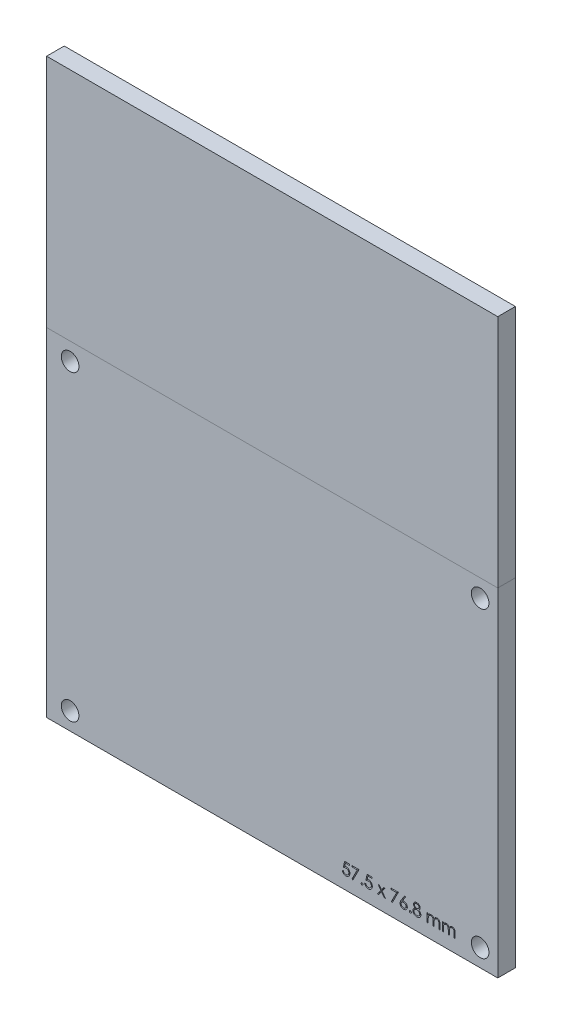
SolidWorks part; units mm, degrees
ref_plane "Front Plane" through (0, 0, 0) normal (0, 0, 1) x (1, 0, 0)
ref_plane "Top Plane" through (0, 0, 0) normal (0, 1, 0) x (1, 0, 0)
ref_plane "Right Plane" through (0, 0, 0) normal (1, 0, 0) x (0, 0, -1)
sketch "Sketch1" plane through (0, 0, 0) normal (0, 0, 1) x (1, 0, 0)
  line L1 (-38.4, 28.75) -> (38.4, 28.75)
  line L2 (-38.4, 28.75) -> (-38.4, -28.75)
  line L3 (-38.4, -28.75) -> (38.4, -28.75)
  line L4 (38.4, 28.75) -> (38.4, -28.75)
  line L5 (-38.4, 28.75) -> (38.4, -28.75) construction
  line L6 (-38.4, -28.75) -> (38.4, 28.75) construction
  dimension "D1" = 57.5
  dimension "D2" = 76.8
  dimension "D3" = 28.75
  dimension "D4" = 38.4
extrude "Boss-Extrude1" add sketch "Sketch1" along normal blind 3 contours L1 L4 L3 L2
sketch "Sketch2" plane through (0, 0, 3) normal (0, 0, 1) x (1, 0, 0)
  line L0 (1.65, 0) -> (-1.65, 0) construction
  line L3 (38.4, 28.75) -> (38.4, -28.75) construction
  line L6 (-38.4, -28.75) -> (38.4, -28.75) construction
  line L7 (-38.4, 28.75) -> (38.4, 28.75) construction
  line L9 (-38.4, 28.75) -> (-38.4, -28.75) construction
  circle A0 centre (-34.4, 25.75) radius 1.5
  circle A1 centre (-34.4, -25.75) radius 1.5
  circle A4 centre (35.4, 25.75) radius 1.5
  circle A5 centre (35.4, -25.75) radius 1.5
  dimension "D1" = 3
  dimension "D2" = 1.5
  dimension "D3" = 2.5
  dimension "D4" = 3
  dimension "D5" = 3
  dimension "D6" = 1.5
  dimension "D7" = 1.5
  dimension "D8" = 1.5
  dimension "D9" = 1.5
extrude "Cut-Extrude1" cut sketch "Sketch2" against normal through all both and the other way through all
sketch "Sketch4" plane through (0, 0, 3) normal (0, 0, 1) x (1, 0, 0)
  text T0 "57.5 x 76.8 mm\r\n" font "Century Gothic" height 2
extrude "Cut-Extrude2" cut sketch "Sketch4" against normal blind 1
sketch "Sketch5" plane through (0, 28.75, 0) normal (0, 1, 0) x (1, 0, 0)
  line L1 (38.4, -3) -> (-38.4, -3)
  line L2 (38.4, -3) -> (38.4, 0)
  line L3 (38.4, 0) -> (-38.4, 0)
  line L4 (-38.4, -3) -> (-38.4, 0)
extrude "Boss-Extrude2" add sketch "Sketch5" along normal blind 40 separate body
